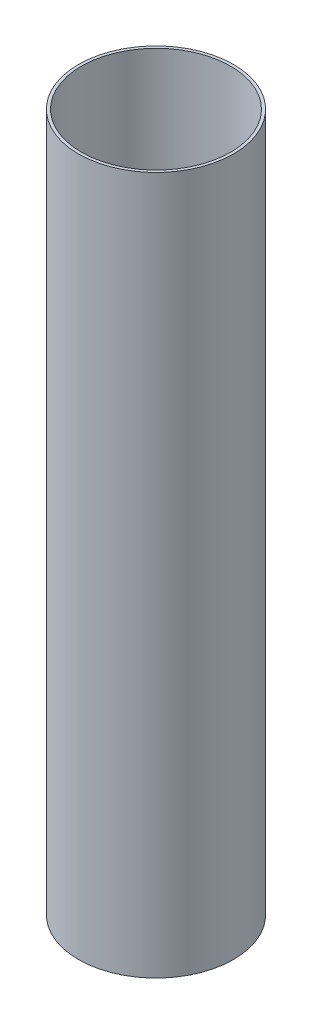
SolidWorks part; units mm, degrees
ref_plane "Front" through (0, 0, 0) normal (0, 0, 1) x (1, 0, 0)
ref_plane "Top" through (0, 0, 0) normal (0, 1, 0) x (1, 0, 0)
ref_plane "Right" through (0, 0, 0) normal (1, 0, 0) x (0, 0, -1)
sketch "Sketch1" plane through (0, 0, 0) normal (0, 1, 0) x (1, 0, 0)
  circle A0 centre (0, 0) radius 101.6
  circle A1 centre (0, 0) radius 97.79
  dimension "D1" = 203.2
  dimension "D2" = 3.81
extrude "Boss-Extrude1" add sketch "Sketch1" along normal mid plane 914.4
